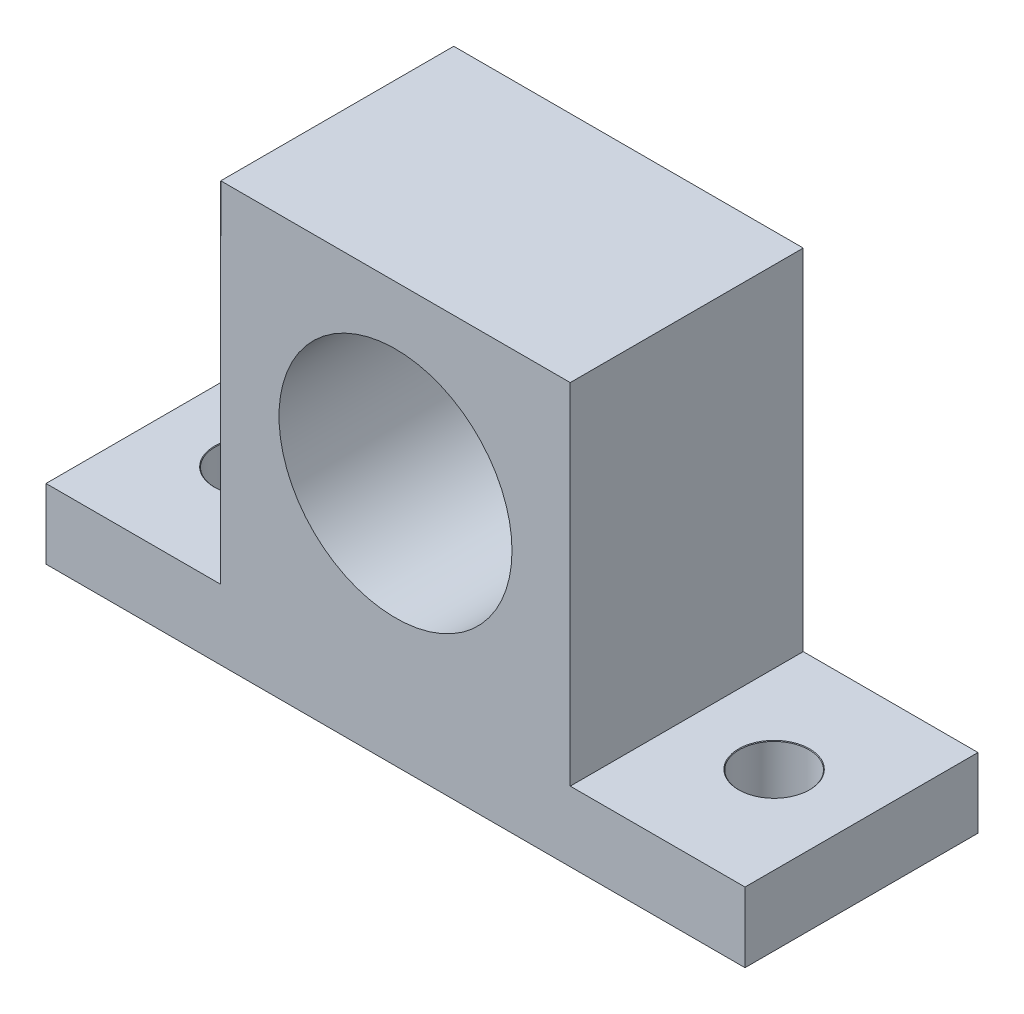
SolidWorks part; units mm, degrees
ref_plane "Front Plane" through (0, 0, 0) normal (0, 0, 1) x (1, 0, 0)
ref_plane "Top Plane" through (0, 0, 0) normal (0, 1, 0) x (1, 0, 0)
ref_plane "Right Plane" through (0, 0, 0) normal (1, 0, 0) x (0, 0, -1)
sketch "Sketch1" plane through (0, 0, 0) normal (0, 1, 0) x (1, 0, 0)
  line L1 (-136.0465, -42.8239) -> (-106.0465, -42.8239)
  line L2 (-136.0465, -42.8239) -> (-136.0465, -52.8239)
  line L3 (-136.0465, -52.8239) -> (-106.0465, -52.8239)
  line L4 (-106.0465, -42.8239) -> (-106.0465, -52.8239)
  dimension "D1" = 30
  dimension "D2" = 10
extrude "Boss-Extrude1" add sketch "Sketch1" along normal blind 3
sketch "Sketch2" plane through (0, 3, 0) normal (0, 1, 0) x (1, 0, 0)
  line L0 (-106.0465, -42.8239) -> (-136.0465, -42.8239) construction
  line L1 (-128.5465, -42.8239) -> (-113.5465, -42.8239)
  line L2 (-128.5465, -42.8239) -> (-128.5465, -52.8239)
  line L3 (-128.5465, -52.8239) -> (-113.5465, -52.8239)
  line L4 (-113.5465, -42.8239) -> (-113.5465, -52.8239)
  line L5 (-136.0465, -52.8239) -> (-106.0465, -52.8239) construction
  line L6 (-136.0465, -42.8239) -> (-136.0465, -52.8239) construction
  line L7 (-106.0465, -52.8239) -> (-106.0465, -42.8239) construction
  line M4 (-136.0465, -52.8239) -> (-106.0465, -52.8239)
  line M6 (-106.0465, -42.8239) -> (-136.0465, -42.8239)
  dimension "D1" = 7.5
  dimension "D2" = 7.5
extrude "Boss-Extrude2" add sketch "Sketch2" along normal blind 15 contours L4 L2 M6 M4
sketch "Sketch3" plane through (0, 0, 52.8239) normal (0, 0, 1) x (1, 0, 0)
  line L0 (-128.5465, 18) -> (-113.5465, 3) construction
  line L1 (-113.5465, 3) -> (-113.5465, 18) construction
  line L2 (-113.5465, 18) -> (-128.5465, 3) construction
  circle A0 centre (-121.0465, 10.5) radius 5
  dimension "D1" = 10
extrude "Cut-Extrude1" cut sketch "Sketch3" against normal through all
sketch "Sketch6" plane through (0, 3, 0) normal (0, 1, 0) x (1, 0, 0)
  line L0 (-136.0465, -42.8239) -> (-128.5465, -52.8239) construction
  line L1 (-128.5465, -42.8239) -> (-136.0465, -52.8239) construction
  point P10 (-132.2965, -47.8239)
hole_wizard "Ø3.0mm Dowel Hole1" positions "Sketch6" profile "Sketch7" hole size "Ø3.0" standard "ISO" end condition through all
sketch "Sketch7" plane through (-132.2965, 3, 47.8239) normal (1, 0, 0) x (0, 0, 1)
  line L0 (0, 0) -> (0, 3)
  line L1 (0, 3) -> (1.5, 3)
  line L2 (1.5, 3) -> (1.5, 0.025)
  line L3 (1.5, 0.025) -> (1.525, 0)
  line L5 (1.525, 0) -> (0, 0)
  line L6 (-1.5, 0.025) -> (-1.525, 0) construction
  line L11 (0, -6.35) -> (0, 107.95) construction
  dimension "Thru Hole Dia." = 3
  dimension "Thru Hole Depth" = 3
  dimension "Near C'Sink Dia." = 3.05
  dimension "Near C'Sink Angle" = 90
sketch "Sketch8" plane through (0, 18, 0) normal (0, 1, 0) x (1, 0, 0)
  line L0 (-121.0465, -42.8239) -> (-121.0465, -52.8239) construction
  line L1 (-113.5465, -42.8239) -> (-128.5465, -42.8239) construction
  line L2 (-128.5465, -52.8239) -> (-113.5465, -52.8239) construction
ref_plane "Plane1" through (-121.0465, 0, 0) normal (1, 0, 0) x (0, 0, -1)
mirror "Mirror1" about plane through (-121.0465, 0, 0) normal (1, 0, 0) of "Ø3.0mm Dowel Hole1"
